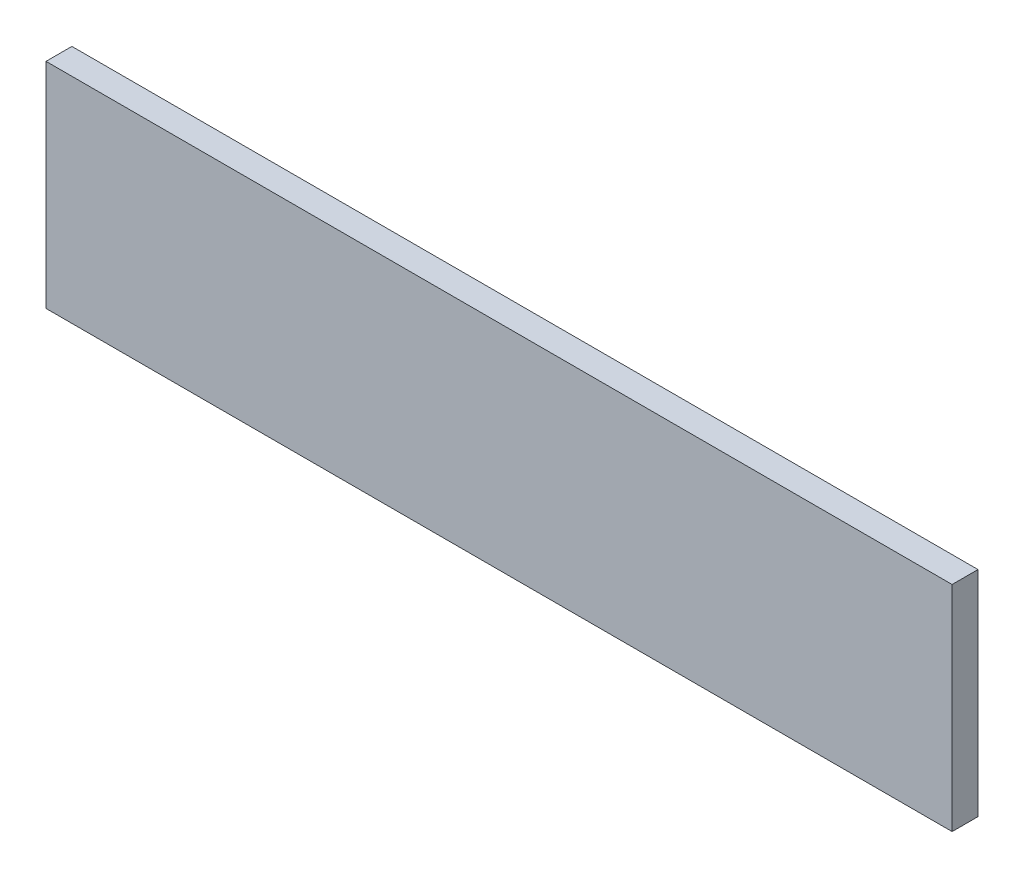
SolidWorks part; units mm, degrees
ref_plane "Front Plane" through (0, 0, 0) normal (0, 0, 1) x (1, 0, 0)
ref_plane "Top Plane" through (0, 0, 0) normal (0, 1, 0) x (1, 0, 0)
ref_plane "Right Plane" through (0, 0, 0) normal (1, 0, 0) x (0, 0, -1)
sketch "Sketch1" plane through (0, 0, 0) normal (1, 0, 0) x (0, 0, -1)
  line L1 (0, 0) -> (3, 0)
  line L2 (0, 0) -> (0, 24.8)
  line L3 (0, 24.8) -> (3, 24.8)
  line L4 (3, 0) -> (3, 24.8)
  dimension "D1" = 24.8
  dimension "D2" = 3
extrude "Boss-Extrude1" add sketch "Sketch1" along normal blind 105
